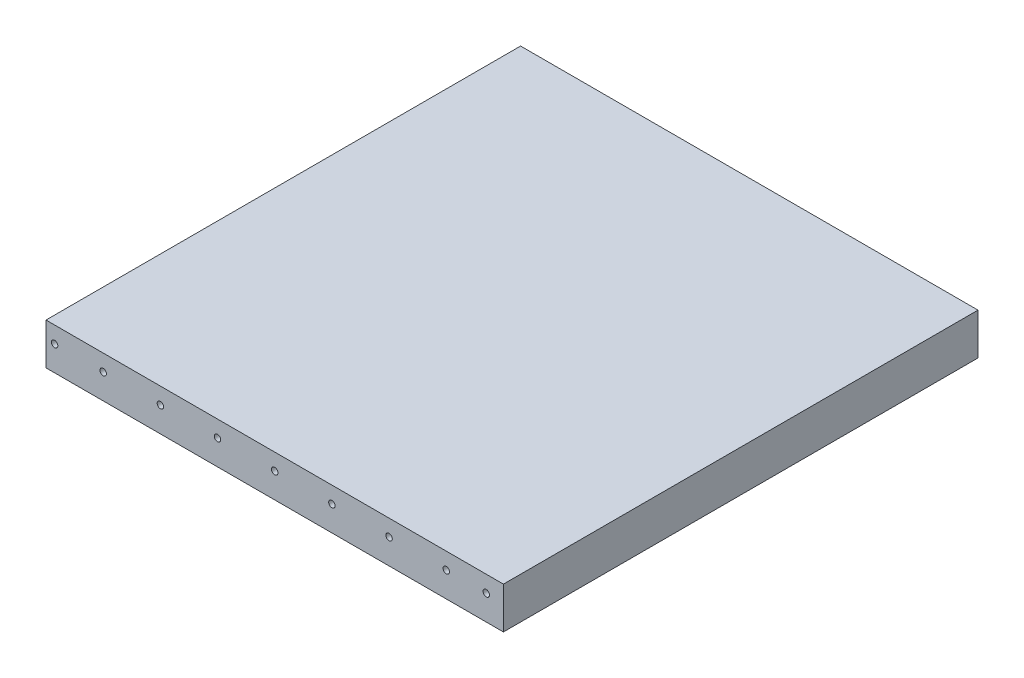
SolidWorks part; units mm, degrees
ref_plane "Front Plane" through (0, 0, 0) normal (0, 0, 1) x (1, 0, 0)
ref_plane "Top Plane" through (0, 0, 0) normal (0, 1, 0) x (1, 0, 0)
ref_plane "Right Plane" through (0, 0, 0) normal (1, 0, 0) x (0, 0, -1)
sketch "Sketch1" plane through (0, 0, 0) normal (0, 0, 1) x (1, 0, 0)
  line L1 (0, 0) -> (2032, 0)
  line L2 (0, 0) -> (0, 184.15)
  line L3 (0, 184.15) -> (2032, 184.15)
  line L4 (2032, 0) -> (2032, 184.15)
extrude "Boss-Extrude1" add sketch "Sketch1" along normal blind 2108.2
sketch "Sketch2" plane through (0, 0, 0) normal (0, 0, 1) x (1, 0, 0)
  circle A0 centre (38.1, 111.125) radius 14.2875
  circle A1 centre (254, 111.125) radius 14.2875
  circle A2 centre (508, 111.125) radius 14.2875
  circle A3 centre (762, 111.125) radius 14.2875
  circle A4 centre (1016, 111.125) radius 14.2875
  circle A5 centre (1270, 111.125) radius 14.2875
  circle A6 centre (1524, 111.125) radius 14.2875
  circle A7 centre (1778, 111.125) radius 14.2875
  circle A8 centre (1955.8, 111.125) radius 14.2875
extrude "Cut-Extrude1" cut sketch "Sketch2" along normal through all
sketch "Sketch3" plane through (0, 0, 0) normal (0, 0, 1) x (1, 0, 0)
  circle A0 centre (38.1, 111.125) radius 14.2875
  circle A1 centre (254, 111.125) radius 14.2875
  circle A2 centre (508, 111.125) radius 14.2875
  circle A3 centre (762, 111.125) radius 14.2875
  circle A4 centre (1016, 111.125) radius 14.2875
  circle A5 centre (1270, 111.125) radius 14.2875
  circle A6 centre (1524, 111.125) radius 14.2875
  circle A7 centre (1778, 111.125) radius 14.2875
  circle A8 centre (1955.8, 111.125) radius 14.2875
